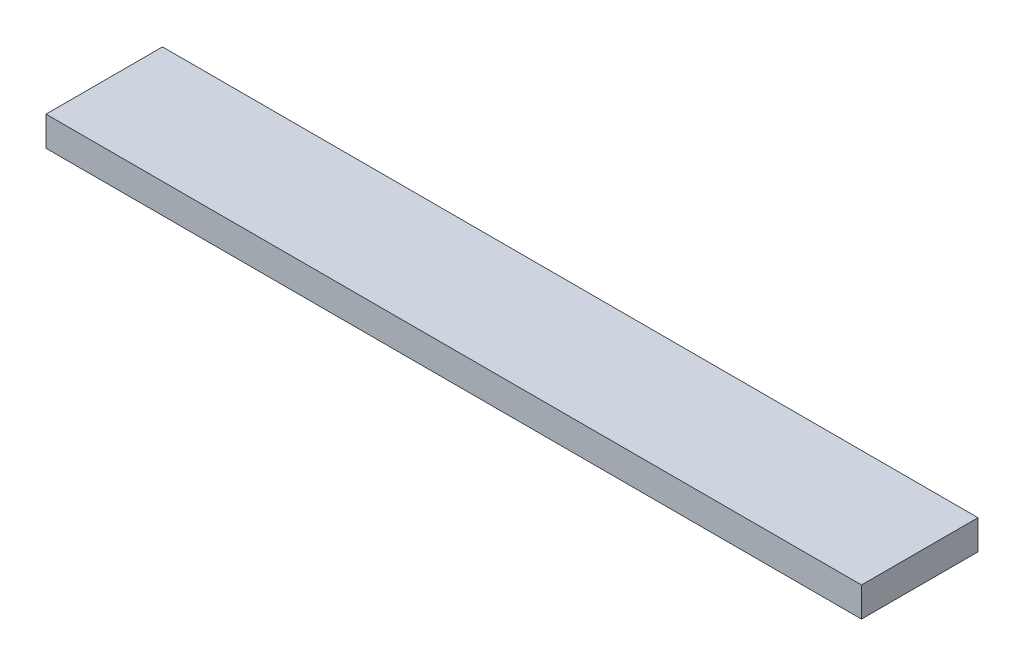
SolidWorks part; units mm, degrees
ref_plane "Plan de face" through (0, 0, 0) normal (0, 0, 1) x (1, 0, 0)
ref_plane "Plan de dessus" through (0, 0, 0) normal (0, 1, 0) x (1, 0, 0)
ref_plane "Plan de droite" through (0, 0, 0) normal (1, 0, 0) x (0, 0, -1)
sketch "Esquisse1" plane through (0, 0, 0) normal (0, 1, 0) x (1, 0, 0)
  line L0 (-87.5, 0) -> (0, 0) construction
  line L1 (-87.5, 12.5) -> (87.5, 12.5)
  line L2 (-87.5, 12.5) -> (-87.5, -12.5)
  line L3 (-87.5, -12.5) -> (87.5, -12.5)
  line L4 (87.5, 12.5) -> (87.5, -12.5)
  line L5 (0, 0) -> (87.5, 0) construction
  dimension "D1" = 25
  dimension "D2" = 175
extrude "Boss.-Extru.1" add sketch "Esquisse1" along normal blind 6.35
